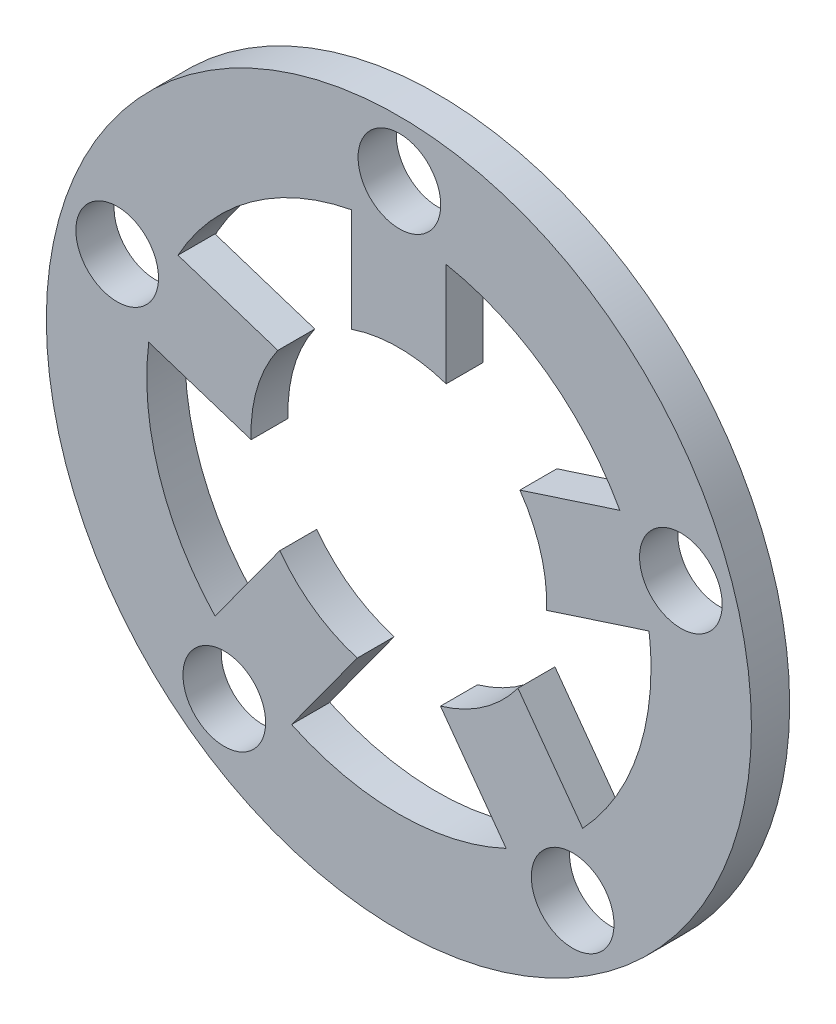
SolidWorks part; units mm, degrees
ref_plane "Front Plane" through (0, 0, 0) normal (0, 0, 1) x (1, 0, 0)
ref_plane "Top Plane" through (0, 0, 0) normal (0, 1, 0) x (1, 0, 0)
ref_plane "Right Plane" through (0, 0, 0) normal (1, 0, 0) x (0, 0, -1)
sketch "Sketch2" plane through (0, 0, 0) normal (0, 0, 1) x (1, 0, 0)
  circle A0 centre (0, 0) radius 20.8362
  circle A1 centre (0, 0) radius 29.1384
  point P9 (0, 0)
extrude "Ring" add sketch "Sketch2" along normal blind 2.6536 and the other way blind 0.508
sketch "Sketch4" plane through (0, 0, 0) normal (0, 0, 1) x (1, 0, 0)
  line L0 (0, 0) -> (0, 20.8362) construction
  line L2 (-3.9084, 20.8362) -> (3.9084, 20.8362)
  line L3 (-3.9084, 20.8362) -> (-3.9084, 10.9642)
  line L4 (-3.9084, 10.9642) -> (3.9084, 10.9642)
  line L5 (3.9084, 20.8362) -> (3.9084, 10.9642)
  line L6 (-3.9084, 20.8362) -> (3.9084, 10.9642) construction
  line L7 (-3.9084, 10.9642) -> (3.9084, 20.8362) construction
  circle A1 centre (0, 0) radius 20.8362 construction
  point P4 (0, 15.9002)
  point P10 (0, 10.9642)
  point P11 (0, 0)
  point P12 (0, 0)
  point P13 (0, 0)
  point P14 (3.9084, 5.186)
extrude "Teeth" add sketch "Sketch4" along normal through all and the other way blind 0.4013
pattern_circular "CirPattern1" count 5 every 72 about axis through (0, 0, 0) along (0, 0, 1) of "Teeth"
sketch "Sketch6" plane through (0, 0, -0.508) normal (0, 0, -1) x (-1, 0, 0)
  circle A0 centre (-23.3072, 7.5287) radius 3.4162
  point P2 (0, 0)
  point P3 (0, 0)
  point P4 (0, 0)
  point P5 (0, 0)
  point P6 (0, 0)
  point P9 (-23.3072, 7.5287)
  point P10 (0, 0)
extrude "Cut-Extrude1" cut sketch "Sketch6" against normal blind 8.89
pattern_circular "CirPattern2" count 5 over 360 about axis through (0, 0, 0) along (0, 0, 1) of "Cut-Extrude1"
sketch "Sketch7" plane through (0, 0, 0) normal (0, 0, 1) x (1, 0, 0)
  circle A0 centre (0, 0.3404) radius 12.2186
extrude "Cut-Extrude3" cut sketch "Sketch7" against normal blind 5.08 and the other way blind 7.874
